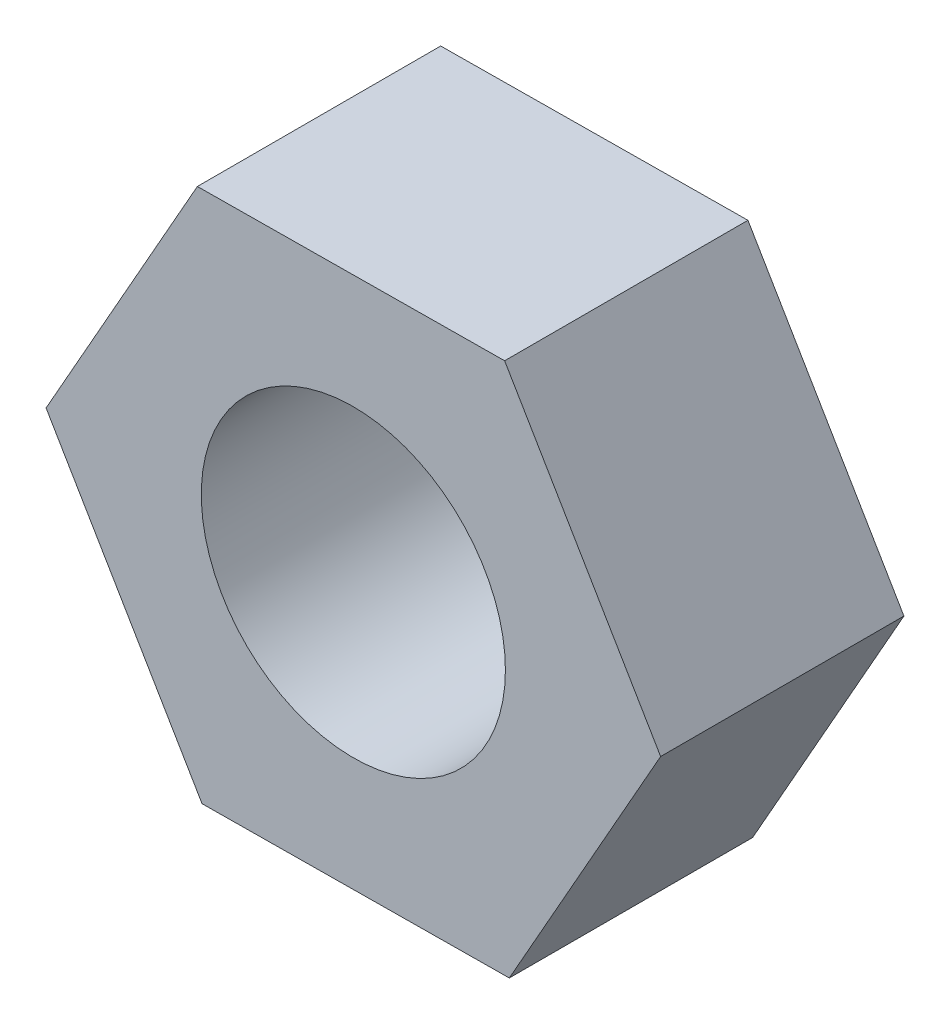
SolidWorks part; units mm, degrees
ref_plane "前视基准面" through (0, 0, 0) normal (0, 0, 1) x (1, 0, 0)
ref_plane "上视基准面" through (0, 0, 0) normal (0, 1, 0) x (1, 0, 0)
ref_plane "右视基准面" through (0, 0, 0) normal (1, 0, 0) x (0, 0, -1)
sketch "草图1" plane through (0, 0, 0) normal (0, 0, 1) x (1, 0, 0)
  line L1 (2.0515, -3.4821) -> (4.0413, 0.0356)
  line L2 (4.0413, 0.0356) -> (1.9898, 3.5177)
  line L3 (1.9898, 3.5177) -> (-2.0515, 3.4821)
  line L4 (-2.0515, 3.4821) -> (-4.0413, -0.0356)
  line L5 (-4.0413, -0.0356) -> (-1.9898, -3.5177)
  line L6 (-1.9898, -3.5177) -> (2.0515, -3.4821)
  circle A0 centre (0, 0) radius 3.5 construction
  circle A1 centre (0, 0) radius 2
extrude "凸台-拉伸1" add sketch "草图1" along normal blind 3.2
